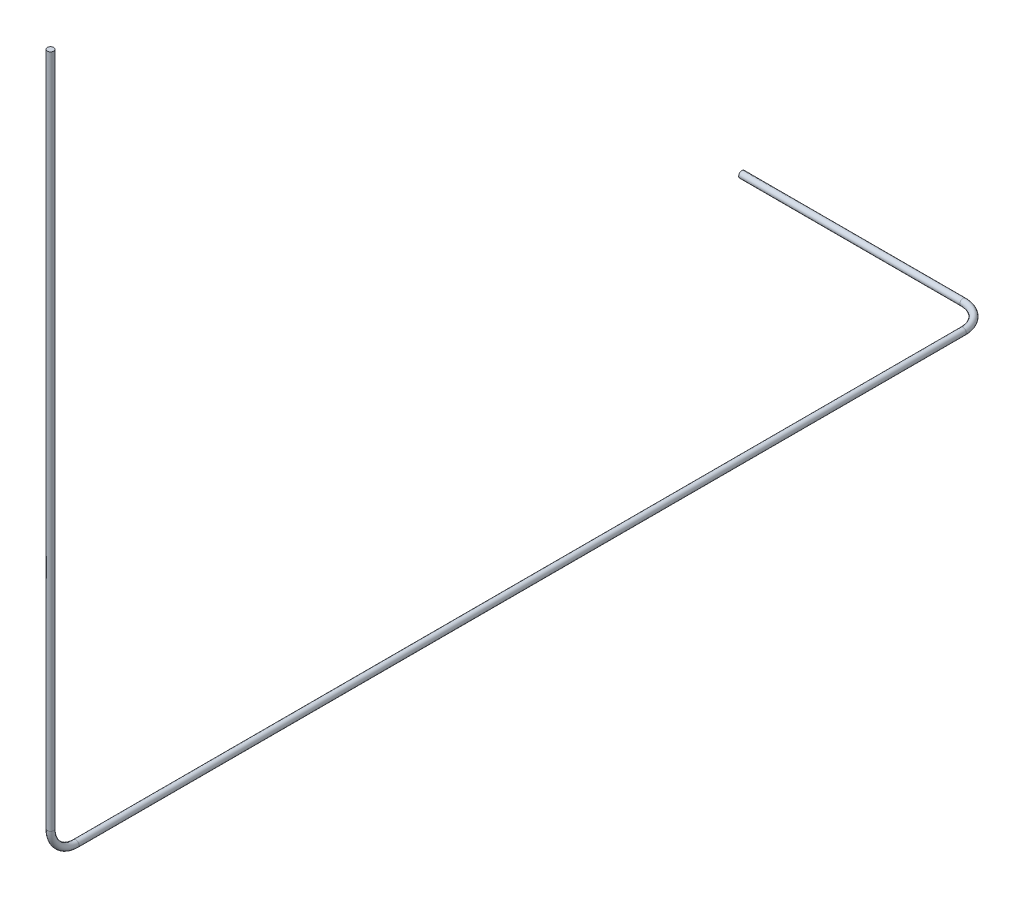
SolidWorks part; units mm, degrees
ref_plane "Alzado" through (0, 0, 0) normal (0, 0, 1) x (1, 0, 0)
ref_plane "Planta" through (0, 0, 0) normal (0, 1, 0) x (1, 0, 0)
ref_plane "Vista lateral" through (0, 0, 0) normal (1, 0, 0) x (0, 0, -1)
sketch3d "Croquis3D2"
  line L0 (99.4628, -956.7476, 1866.72) -> (537.0205, -956.7476, 1866.72)
  line L3 (587.0205, -956.7476, 1916.72) -> (587.0205, -956.7476, 3672.0902)
  line L4 (587.0205, -906.7476, 3722.0902) -> (587.0205, 428.8121, 3722.0902)
  arc A0 (537.0205, -956.7476, 1866.72) -> (587.0205, -956.7476, 1916.72) centre (537.0205, -956.7476, 1916.72) ccw
  arc A1 (587.0205, -956.7476, 3672.0902) -> (587.0205, -906.7476, 3722.0902) centre (587.0205, -906.7476, 3672.0902) ccw
  point P4 (587.0205, -956.7476, 1866.72)
  point P5 (537.0205, -1006.7476, 1916.72)
  point P10 (587.0205, -956.7476, 3722.0902)
  point P11 (537.0205, -906.7476, 3672.0902)
  dimension "D1" = 50
  dimension "D2" = 487.5577
  dimension "D3" = 1855.3702
  dimension "D4" = 1385.5597
sweep "Barrer3" add path "Croquis3D2" circular profile diameter 12.7 parameters "D3"=12.7
